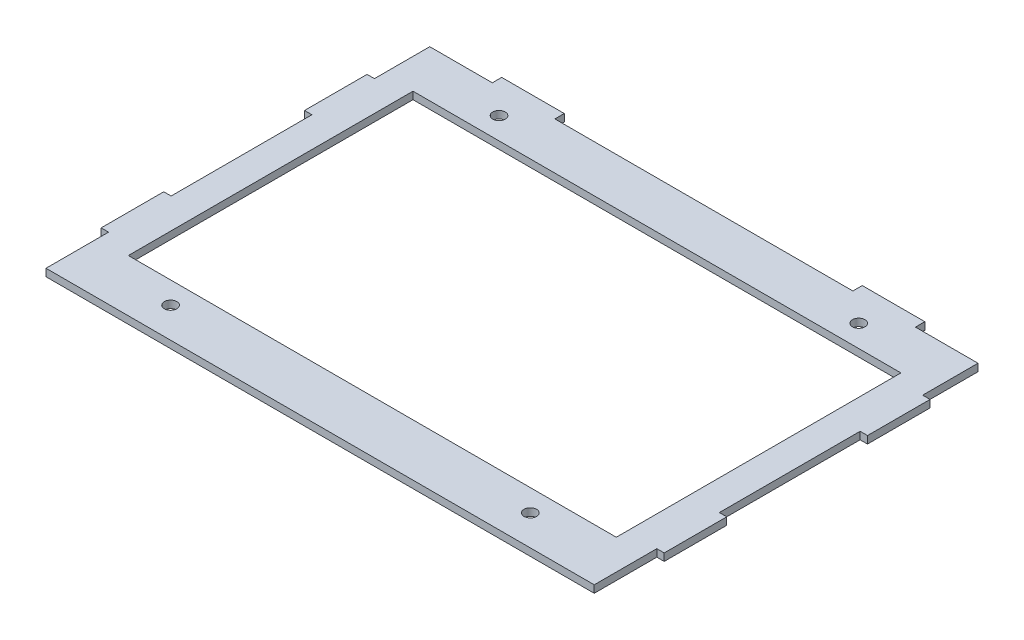
SolidWorks part; units mm, degrees
ref_plane "Front Plane" through (0, 0, 0) normal (0, 0, 1) x (1, 0, 0)
ref_plane "Top Plane" through (0, 0, 0) normal (0, 1, 0) x (1, 0, 0)
ref_plane "Right Plane" through (0, 0, 0) normal (1, 0, 0) x (0, 0, -1)
sketch "Sketch1" plane through (0, 0, 0) normal (0, 1, 0) x (1, 0, 0)
  line L0 (-93.5228, 66.8838) -> (-73.5228, 66.8838)
  line L3 (-93.5228, -55.8062) -> (81.7528, -55.8062)
  line L5 (-73.5228, 66.8838) -> (-73.5228, 69.8838)
  line L6 (-73.5228, 69.8838) -> (-53.5228, 69.8838)
  line L7 (-53.5228, 69.8838) -> (-53.5228, 66.8838)
  line L8 (-53.5228, 66.8838) -> (41.7528, 66.8838)
  line L9 (41.7528, 66.8838) -> (41.7528, 69.8838)
  line L10 (41.7528, 69.8838) -> (61.7528, 69.8838)
  line L11 (61.7528, 69.8838) -> (61.7528, 66.8838)
  line L12 (61.7528, 66.8838) -> (81.7528, 66.8838)
  line L13 (-93.5228, 66.8838) -> (-93.5228, 49.1938)
  line L14 (-93.5228, 49.1938) -> (-95.885, 49.1938)
  line L15 (-95.885, 49.1938) -> (-95.885, 29.1938)
  line L16 (-95.885, 29.1938) -> (-93.5228, 29.1938)
  line L17 (-93.5228, 29.1938) -> (-93.5228, -15.8062)
  line L18 (-93.5228, -15.8062) -> (-95.885, -15.8062)
  line L19 (-95.885, -15.8062) -> (-95.885, -35.8062)
  line L20 (-95.885, -35.8062) -> (-93.5228, -35.8062)
  line L21 (-93.5228, -35.8062) -> (-93.5228, -55.8062)
  line L22 (81.7528, 66.8838) -> (81.7528, 49.1938)
  line L23 (81.7528, 49.1938) -> (84.115, 49.1938)
  line L24 (84.115, 49.1938) -> (84.115, 29.1938)
  line L25 (84.115, 29.1938) -> (81.7528, 29.1938)
  line L26 (81.7528, 29.1938) -> (81.7528, -15.8062)
  line L27 (81.7528, -15.8062) -> (84.115, -15.8062)
  line L28 (84.115, -15.8062) -> (84.115, -35.8062)
  line L29 (84.115, -35.8062) -> (81.7528, -35.8062)
  line L30 (81.7528, -35.8062) -> (81.7528, -55.8062)
  dimension "D2" = 20
  dimension "D3" = 20
  dimension "D4" = 20
  dimension "D5" = 20
  dimension "D6" = 125.69
  dimension "D7" = 3
  dimension "D8" = 3
  dimension "D9" = 3
  dimension "D10" = 20
  dimension "D11" = 20
  dimension "D12" = 20
  dimension "D13" = 20
  dimension "D14" = 20
  dimension "D15" = 20
  dimension "D16" = 45
  dimension "D17" = 2.3622
  dimension "D18" = 2.3622
  dimension "D19" = 2.3622
  dimension "D20" = 2.3622
  dimension "D21" = 2.3622
  dimension "D22" = 2.3622
  dimension "D23" = 2.3622
  dimension "D24" = 2.3622
  dimension "D25" = 45
extrude "Boss-Extrude1" add sketch "Sketch1" along normal blind 2.3622
sketch "Sketch2" plane through (0, 2.3622, 0) normal (0, 1, 0) x (1, 0, 0)
  line L0 (-53.5228, 69.8838) -> (-73.5228, 69.8838) construction
  line L1 (-83.885, 51.8838) -> (72.115, 51.8838)
  line L2 (-83.885, 51.8838) -> (-83.885, -39.1162)
  line L3 (-83.885, -39.1162) -> (72.115, -39.1162)
  line L4 (72.115, 51.8838) -> (72.115, -39.1162)
  line L5 (-95.885, 49.1938) -> (-95.885, 29.1938) construction
  circle A0 centre (-63.385, 58.8838) radius 2
  circle A1 centre (51.615, 58.8838) radius 2
  circle A2 centre (-63.385, -46.1162) radius 2
  circle A3 centre (51.615, -46.1162) radius 2
  dimension "D5" = 4
  dimension "D6" = 4
  dimension "D7" = 4
  dimension "D8" = 4
  dimension "D9" = 105
  dimension "D1" = 156
  dimension "D2" = 91
  dimension "D3" = 18
  dimension "D4" = 12
  dimension "D10" = 105
  dimension "D11" = 115
  dimension "D12" = 115
  dimension "D13" = 20.5
  dimension "D14" = 7
extrude "Cut-Extrude1" cut sketch "Sketch2" against normal through all
